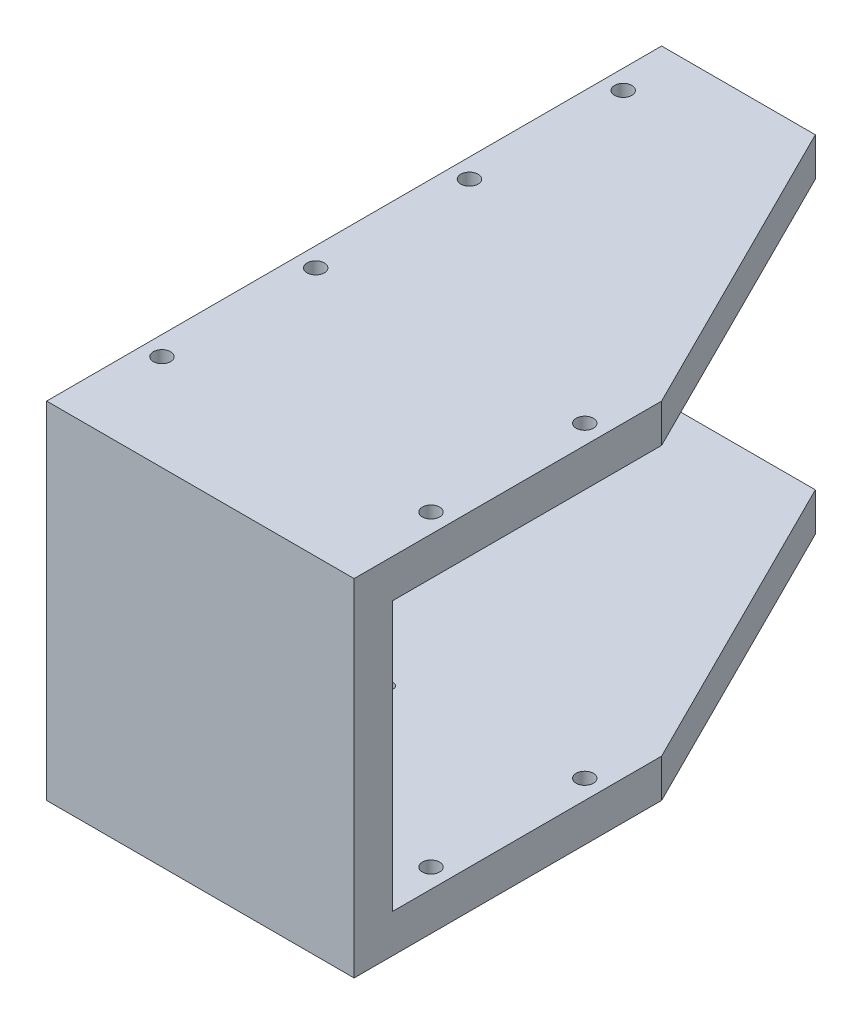
SolidWorks part; units mm, degrees
material "ABS"
ref_plane "Alzado" through (0, 0, 0) normal (0, 0, 1) x (1, 0, 0)
ref_plane "Planta" through (0, 0, 0) normal (0, 1, 0) x (1, 0, 0)
ref_plane "Vista lateral" through (0, 0, 0) normal (1, 0, 0) x (0, 0, -1)
sketch "Croquis1" plane through (0, 0, 0) normal (0, 1, 0) x (1, 0, 0)
  line L0 (0, 0) -> (0, 80)
  line L1 (0, 80) -> (-40, 160)
  line L2 (-40, 160) -> (-80, 160)
  line L3 (-80, 160) -> (-80, 0)
  line L4 (-80, 0) -> (0, 0)
  dimension "D1" = 80
  dimension "D2" = 80
  dimension "D3" = 160
  dimension "D4" = 40
extrude "Saliente-Extruir1" add sketch "Croquis1" along normal blind 10
sketch "Croquis2" plane through (0, 10, 0) normal (0, 1, 0) x (1, 0, 0)
  line L0 (-80, 0) -> (-80, 10)
  line L1 (-80, 160) -> (-80, 0) construction
  line L2 (-80, 10) -> (0, 10)
  line L3 (0, 0) -> (0, 80) construction
  line L4 (0, 10) -> (0, 0)
  line L5 (0, 0) -> (-80, 0)
  dimension "D1" = 10
extrude "Saliente-Extruir2" add sketch "Croquis2" along normal blind 70
sketch "Croquis3" plane through (0, 80, 0) normal (0, 1, 0) x (1, 0, 0)
  line L5 (-80, 0) -> (0, 0)
  line L6 (-80, 160) -> (-80, 0)
  line L7 (-40, 160) -> (-80, 160)
  line L8 (0, 80) -> (-40, 160)
  line L9 (0, 0) -> (0, 80)
  line L10 (-80, 0) -> (0, 0)
  line L11 (-80, 160) -> (-80, 0)
  line L12 (-40, 160) -> (-80, 160)
  line L13 (0, 80) -> (-40, 160)
  line L14 (0, 0) -> (0, 80)
  dimension "D1" = 0
extrude "Saliente-Extruir3" add sketch "Croquis3" along normal blind 10
sketch "Croquis4" plane through (0, 90, 0) normal (0, 1, 0) x (1, 0, 0)
  line L0 (-80, 25) -> (-75, 25) construction
  line L1 (-80, 160) -> (-80, 0) construction
  line L2 (-75, 25) -> (-5, 25) construction
  line L3 (-5, 25) -> (0, 25) construction
  line L4 (0, 0) -> (0, 80) construction
  line L5 (-80, 0) -> (0, 0) construction
  line L6 (-75, 25) -> (-75, 65) construction
  line L7 (-75, 65) -> (-5, 65) construction
  line L8 (-5, 65) -> (-5, 25) construction
  line L9 (-75, 65) -> (-75, 105) construction
  line L10 (-75, 105) -> (-75, 145) construction
  line L11 (-75, 145) -> (-75, 160) construction
  line L12 (-40, 160) -> (-80, 160) construction
  circle A0 centre (-75, 25) radius 2.25
  circle A1 centre (-5, 25) radius 2.25
  circle A2 centre (-5, 65) radius 2.25
  circle A3 centre (-75, 65) radius 2.25
  circle A4 centre (-75, 145) radius 2.25
  circle A5 centre (-75, 105) radius 2.25
  dimension "D3" = 4.5
  dimension "D1" = 25
  dimension "D2" = 5
  dimension "D4" = 40
  dimension "D5" = 15
  dimension "D6" = 40
extrude "Cortar-Extruir1" cut sketch "Croquis4" against normal through all
sketch "Croquis5" plane through (0, 0, 0) normal (0, -1, 0) x (1, 0, 0)
  line L0 (-80, 0) -> (0, 0) construction
  line L1 (0, 0) -> (0, -80) construction
  circle A0 centre (-28.57, -29.76) radius 1.4
  circle A1 centre (-51.43, -60.24) radius 1.4
  dimension "D1" = 29.76
  dimension "D2" = 28.57
  dimension "D3" = 22.86
  dimension "D4" = 30.48
  dimension "D5" = 2.8
extrude "Cortar-Extruir2" cut sketch "Croquis5" against normal up to next
